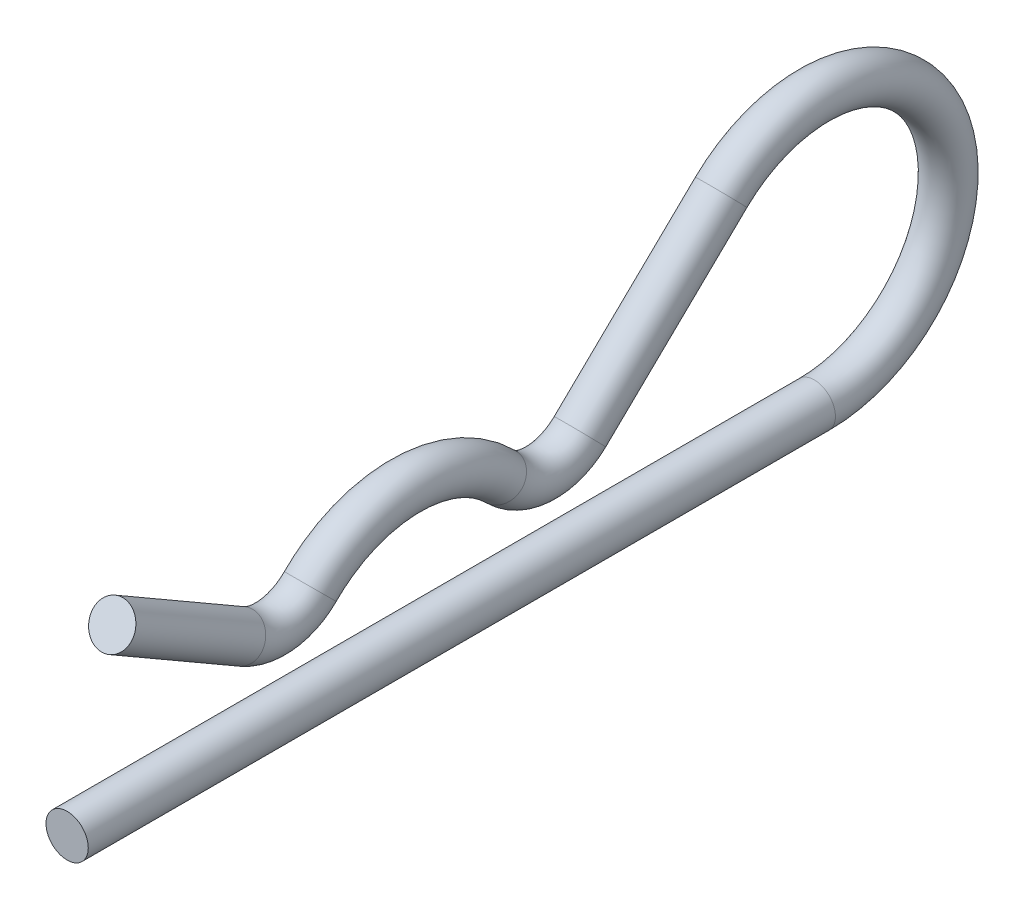
SolidWorks part; units mm, degrees
ref_plane "Front" through (0, 0, 0) normal (0, 0, 1) x (1, 0, 0)
ref_plane "Top" through (0, 0, 0) normal (0, 1, 0) x (1, 0, 0)
ref_plane "Right" through (0, 0, 0) normal (1, 0, 0) x (0, 0, -1)
sketch "Sketch1" plane through (0, 0, 0) normal (0, 0, 1) x (1, 0, 0)
  circle A0 centre (0, 0) radius 0.5953
  dimension "WireOD" = 1.1906
sketch "Sketch2" plane through (0, 0, 0) normal (1, 0, 0) x (0, 0, -1)
  line L0 (0, 0) -> (21.0344, 0)
  line L1 (5.7183, 3.7703) -> (13.3317, 3.7703) construction
  line L2 (25.4, 0) -> (25.4, 3.7703) construction
  line L3 (25.4, 3.7703) -> (24.8047, 3.7703) construction
  line L5 (25.4, 0) -> (0, 0) construction
  line L6 (4.9246, 2.3955) -> (1.27, 4.5055)
  line L7 (9.525, 3.7703) -> (9.525, 0) construction
  line L13 (18.4118, 6.4791) -> (14.4359, 2.6298)
  circle A0 centre (21.0344, 3.7703) radius 3.175 construction
  arc A1 (12.2038, 2.6532) -> (6.8462, 2.6532) centre (9.525, 0) ccw
  arc A6 (6.8462, 2.6532) -> (4.9246, 2.3955) centre (5.7183, 3.7703) cw
  arc A8 (14.4359, 2.6298) -> (12.2038, 2.6532) centre (13.3317, 3.7703) cw
  arc A9 (21.0344, 0) -> (18.4118, 6.4791) centre (21.0344, 3.7703) ccw
  dimension "D2" = 9.525
  dimension "D1" = 1.5875
  dimension "D11" = 0.5953
  dimension "EyeID" = 6.35
  dimension "D3" = 0.5953
  dimension "D5" = 1.27
  dimension "D9" = 30
  dimension "Length" = 25.4
sweep "Sweep1" add profiles "Sketch1" path "Sketch2"
sketch "Sketch3" plane through (0, 0, 0) normal (1, 0, 0) x (0, 0, -1)
  line L0 (-2.8969, 0) -> (27.788, 0) construction
  line L1 (0, -3.3157) -> (0, 8.0575) construction
equation "\"D11@Sketch2\" = \"WireOD@Sketch1\"/2"
equation "\"D1@Sketch2\" = \"EyeID@Sketch2\"/4"
equation "\"D3@Sketch2\" = \"D11@Sketch2\""
equation "\"D2@Sketch2\" = (\"Length@Sketch2\"-\"EyeID@Sketch2\")/2"
equation "\"D5@Sketch2\" = \"Length@Sketch2\"*.05"
